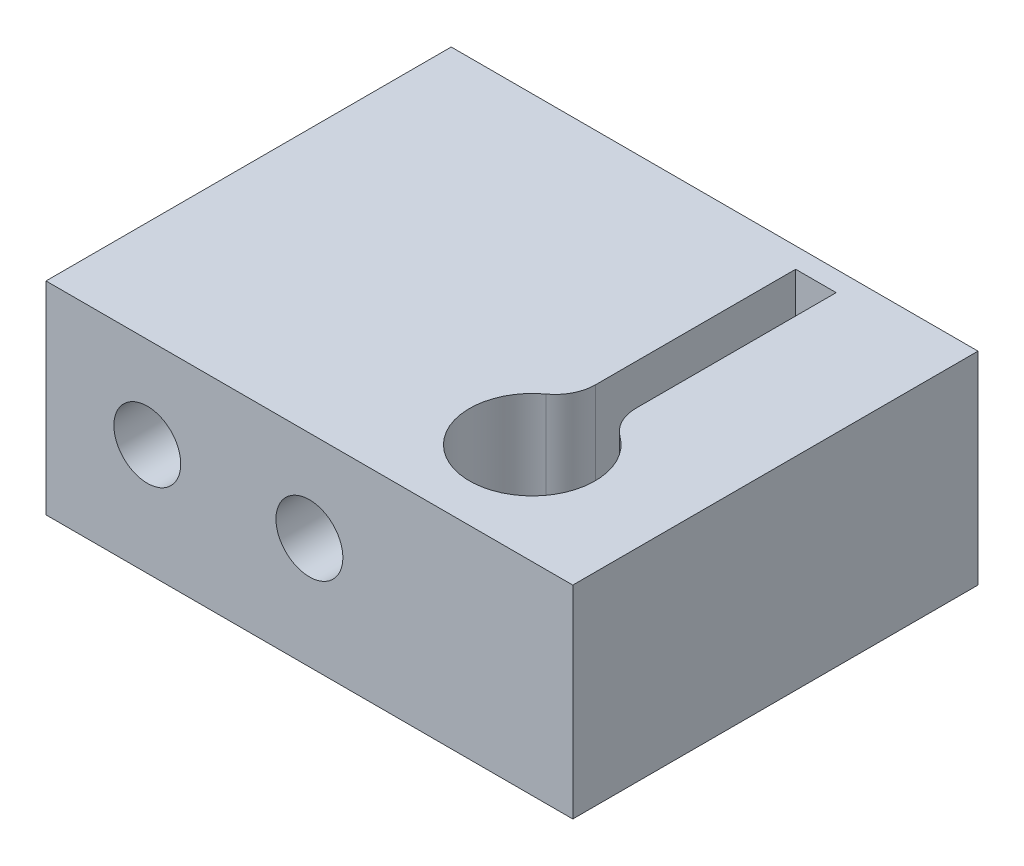
SolidWorks part; units mm, degrees
ref_plane "前视基准面" through (0, 0, 0) normal (0, 0, 1) x (1, 0, 0)
ref_plane "上视基准面" through (0, 0, 0) normal (0, 1, 0) x (1, 0, 0)
ref_plane "右视基准面" through (0, 0, 0) normal (1, 0, 0) x (0, 0, -1)
other "Configuration Table"
sketch "草图1" plane through (0, 0, 0) normal (0, 1, 0) x (1, 0, 0)
  line L1 (-13, -10) -> (13, -10)
  line L2 (-13, -10) -> (-13, 10)
  line L3 (-13, 10) -> (13, 10)
  line L4 (13, -10) -> (13, 10)
  line L5 (0, 10) -> (0, -10) construction
  line L6 (-13, 0) -> (13, 0) construction
  point P0 (0, 0)
  dimension "D1" = 26
  dimension "D2" = 20
extrude "凸台-拉伸1" add sketch "草图1" along normal blind 25
sketch "草图2" plane through (0, 0, 0) normal (0, -1, 0) x (1, 0, 0)
  line L1 (-13, 10) -> (13, 10) construction
  line L2 (13, -10) -> (-13, -10) construction
  line L4 (5, 2.0657) -> (5, -10)
  line L5 (5, -10) -> (7, -10)
  line L6 (7, 2.0657) -> (7, -10)
  line L7 (5, 2.0657) -> (7, 2.0657) construction
  line L8 (13, 10) -> (13, -10) construction
  arc A0 (7, 2.0657) -> (5, 2.0657) centre (6, 5) ccw
  dimension "D1" = 6.2
  dimension "D2" = 7
  dimension "D3" = 5
  dimension "D4" = 2
extrude "切除-拉伸1" cut sketch "草图2" against normal blind 16
fillet "圆角1" radius 2 2 edges at (7, 8, 2.0657) (5, 8, 2.0657)
sketch "草图3" plane through (0, 16, 0) normal (0, -1, 0) x (1, 0, 0)
  circle A0 centre (6, 5) radius 1.25
  dimension "D1" = 2.5
extrude "切除-拉伸2" cut sketch "草图3" against normal through all
sketch "草图4" plane through (0, 0, -10) normal (0, 0, -1) x (-1, 0, 0)
  line L0 (13, 25) -> (13, 0) construction
  line L2 (-13, 25) -> (13, 25) construction
  circle A0 centre (8, 10.5) radius 1.65
  circle A1 centre (0, 10.5) radius 1.65
  dimension "D1" = 3.3
  dimension "D2" = 5
  dimension "D3" = 14.5
  dimension "D4" = 8
extrude "切除-拉伸3" cut sketch "草图4" against normal through all
sketch "草图5" plane through (13, 0, 0) normal (1, 0, 0) x (0, 0, -1)
  line L0 (10, 25) -> (10, 0) construction
  line L1 (-10, 0) -> (10, 0)
  line L2 (-10, 0) -> (-10, 5)
  line L3 (-10, 5) -> (10, 5)
  line L4 (10, 0) -> (10, 5)
  dimension "D1" = 5
extrude "切除-拉伸4" cut sketch "草图5" against normal through all
sketch "草图6" plane through (0, 0, -10) normal (0, 0, -1) x (-1, 0, 0)
  line L0 (13, 25) -> (13, 5) construction
  line L1 (-13, 25) -> (13, 25)
  line L2 (-13, 25) -> (-13, 15)
  line L3 (-13, 15) -> (13, 15)
  line L4 (13, 25) -> (13, 15)
  line L5 (13, 5) -> (-5, 5) construction
  dimension "D1" = 10
extrude "切除-拉伸5" cut sketch "草图6" against normal through all
sketch "草图7" plane through (0, 15, 0) normal (0, 1, 0) x (1, 0, 0)
  line L0 (7, -0.8757) -> (7, 10) construction
  line L1 (5, 10) -> (7, 10)
  line L2 (5, 10) -> (5, 9)
  line L3 (5, 9) -> (7, 9)
  line L4 (7, 10) -> (7, 9)
  dimension "D1" = 1
extrude "凸台-拉伸2" add sketch "草图7" against normal blind 10
